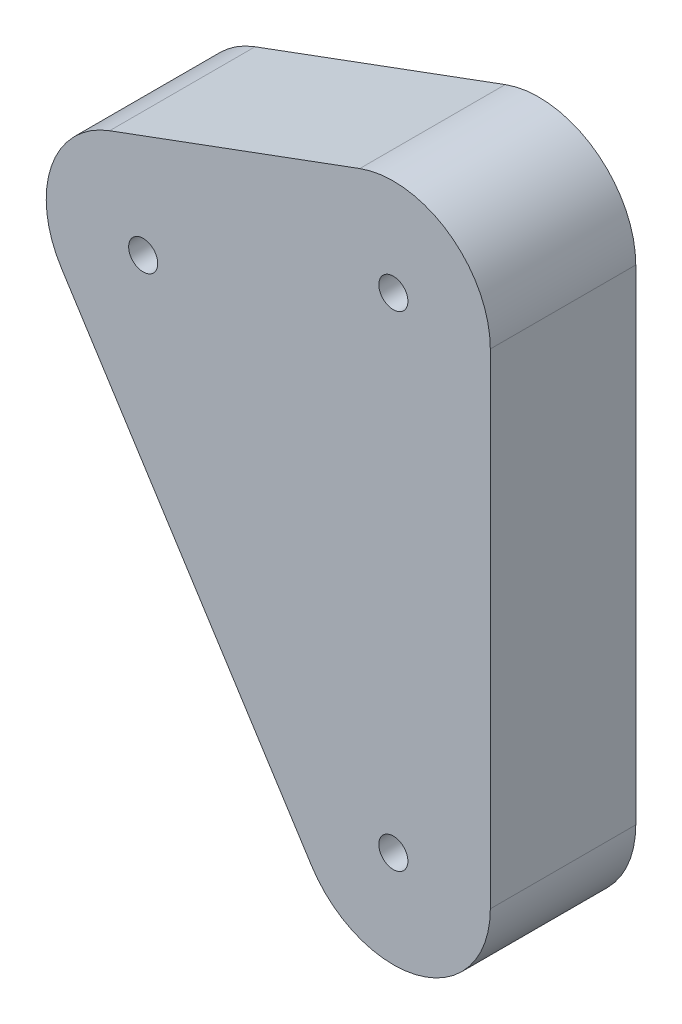
SolidWorks part; units mm, degrees
material "PVC Rigid"
ref_plane "Front Plane" through (0, 0, 0) normal (0, 0, 1) x (1, 0, 0)
ref_plane "Top Plane" through (0, 0, 0) normal (0, 1, 0) x (1, 0, 0)
ref_plane "Right Plane" through (0, 0, 0) normal (1, 0, 0) x (0, 0, -1)
sketch "Sketch1" plane through (0, 0, 0) normal (0, 0, 1) x (1, 0, 0)
  line L3 (-29.2614, 49.8588) -> (-3.4627, 59.3813)
  line L4 (10, 50) -> (10, 0)
  line L5 (-8.4328, -5.3747) -> (-34.2315, 35.1028)
  arc A0 (10, 50) -> (-3.4627, 59.3813) centre (0, 50) ccw
  arc A1 (-29.2614, 49.8588) -> (-34.2315, 35.1028) centre (-25.7987, 40.4775) ccw
  arc A2 (-8.4328, -5.3747) -> (10, 0) centre (0, 0) ccw
  circle A3 centre (-25.7987, 40.4775) radius 1.5
  circle A4 centre (0, 50) radius 1.5
  circle A5 centre (0, 0) radius 1.5
  dimension "D4" = 20
  dimension "D5" = 20
  dimension "D6" = 20
  dimension "D7" = 3
  dimension "D8" = 3
  dimension "D9" = 3
  dimension "D1" = 50
  dimension "D2" = 27.5
  dimension "D3" = 48
extrude "Boss-Extrude1" add sketch "Sketch1" along normal blind 15
